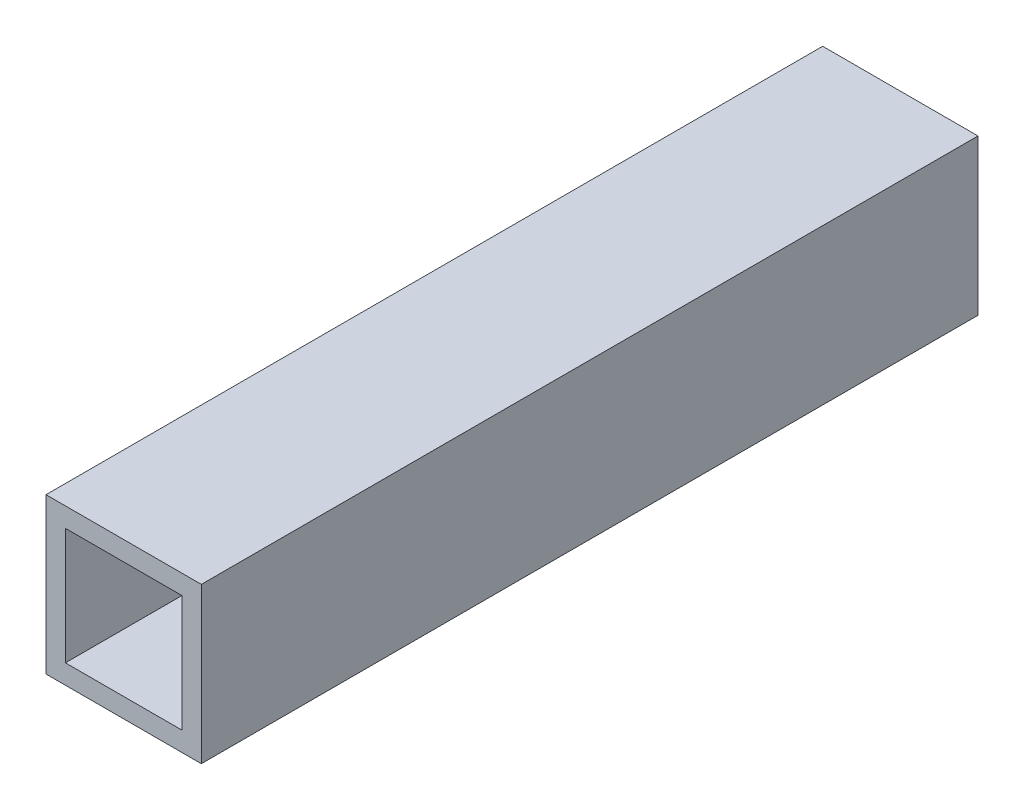
SolidWorks part; units mm, degrees
material "6061 Alloy"
ref_plane "Front Plane" through (0, 0, 0) normal (0, 0, 1) x (1, 0, 0)
ref_plane "Top Plane" through (0, 0, 0) normal (0, 1, 0) x (1, 0, 0)
ref_plane "Right Plane" through (0, 0, 0) normal (1, 0, 0) x (0, 0, -1)
sketch "Sketch2" plane through (0, 0, 0) normal (0, 0, 1) x (1, 0, 0)
  line L1 (-9.525, 9.525) -> (9.525, 9.525)
  line L2 (-9.525, 9.525) -> (-9.525, -9.525)
  line L3 (-9.525, -9.525) -> (9.525, -9.525)
  line L4 (9.525, 9.525) -> (9.525, -9.525)
  line L5 (-9.525, 9.525) -> (9.525, -9.525) construction
  line L6 (-9.525, -9.525) -> (9.525, 9.525) construction
  line L7 (-12.7, 12.7) -> (12.7, 12.7)
  line L8 (-12.7, 12.7) -> (-12.7, -12.7)
  line L9 (-12.7, -12.7) -> (12.7, -12.7)
  line L10 (12.7, 12.7) -> (12.7, -12.7)
  line L11 (-12.7, 12.7) -> (12.7, -12.7) construction
  line L12 (-12.7, -12.7) -> (12.7, 12.7) construction
  point P0 (0, 0)
  point P6 (0, 0)
  dimension "D1" = 25.4
  dimension "D2" = 25.4
  dimension "D3" = 3.175
  dimension "D4" = 3.175
extrude "Boss-Extrude1" add sketch "Sketch2" along normal blind 127
sketch "Sketch3" plane through (0, 0, 0) normal (1, 0, 0) x (0, 0, -1)
  line L0 (-477.1762, 0) -> (16.7996, 0) construction
